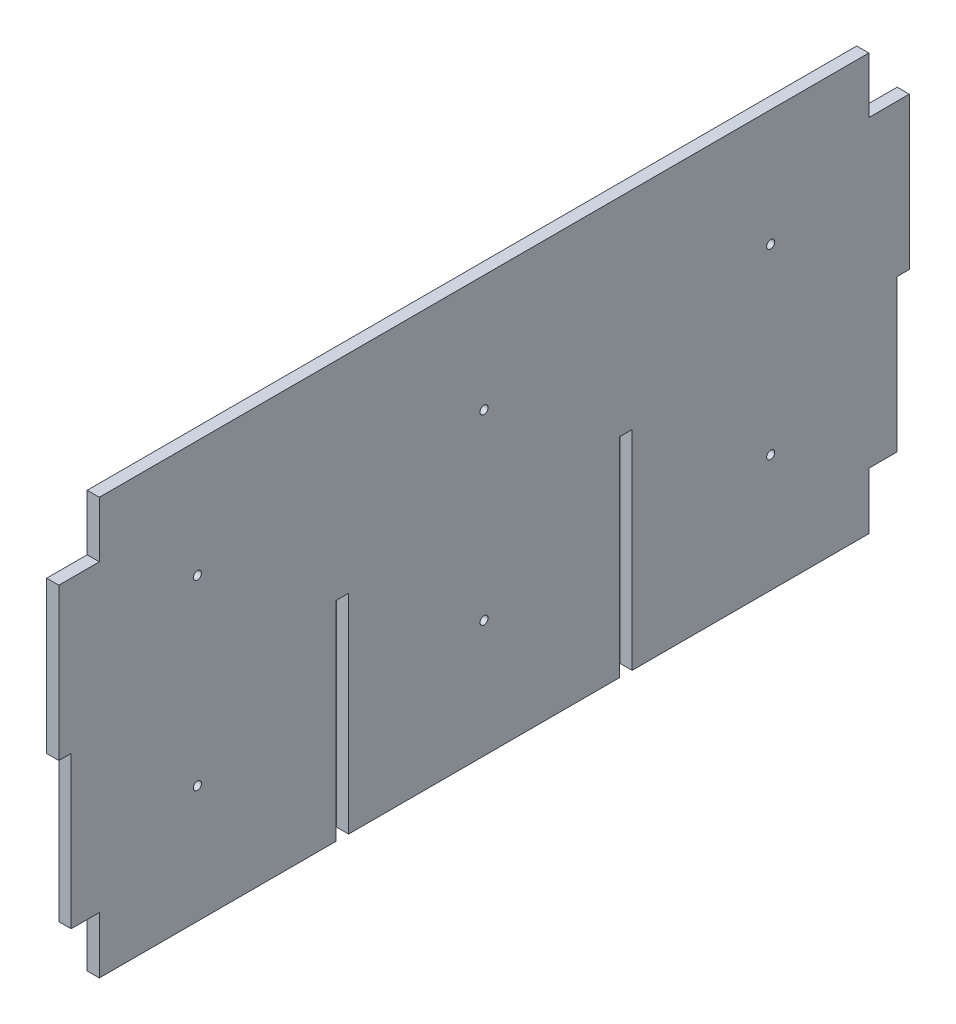
SolidWorks part; units mm, degrees
ref_plane "Front Plane" through (0, 0, 0) normal (0, 0, 1) x (1, 0, 0)
ref_plane "Top Plane" through (0, 0, 0) normal (0, 1, 0) x (1, 0, 0)
ref_plane "Right Plane" through (0, 0, 0) normal (1, 0, 0) x (0, 0, -1)
sketch "Sketch3" plane through (0, 0, 0) normal (1, 0, 0) x (0, 0, -1)
  line L1 (230.9117, 76.9159) -> (650.9117, 76.9159)
  line L2 (230.9117, 76.9159) -> (230.9117, 246.9159)
  line L3 (230.9117, 246.9159) -> (650.9117, 246.9159)
  line L4 (650.9117, 76.9159) -> (650.9117, 246.9159)
  dimension "D1" = 170
  dimension "D2" = 420
extrude "Boss-Extrude2" add sketch "Sketch3" along normal blind 6
sketch "Sketch4" plane through (6, 0, 0) normal (1, 0, 0) x (0, 0, -1)
  line L0 (230.9117, 246.9159) -> (230.9117, 76.9159) construction
  line L1 (230.9117, 161.9159) -> (237.0117, 161.9159)
  line L2 (230.9117, 161.9159) -> (230.9117, 76.9159)
  line L3 (230.9117, 76.9159) -> (237.0117, 76.9159)
  line L4 (237.0117, 161.9159) -> (237.0117, 76.9159)
  line L5 (230.9117, 76.9159) -> (650.9117, 76.9159) construction
  line L6 (650.9117, 76.9159) -> (650.9117, 246.9159) construction
  line L7 (650.9117, 161.9159) -> (644.8117, 161.9159)
  line L8 (650.9117, 161.9159) -> (650.9117, 76.9159)
  line L9 (650.9117, 76.9159) -> (644.8117, 76.9159)
  line L10 (644.8117, 161.9159) -> (644.8117, 76.9159)
  line L11 (650.9117, 246.9159) -> (230.9117, 246.9159) construction
  line L12 (367.8117, 246.9159) -> (374.0117, 246.9159)
  line L13 (367.8117, 246.9159) -> (367.8117, 161.9159)
  line L14 (367.8117, 161.9159) -> (374.0117, 161.9159)
  line L15 (374.0117, 246.9159) -> (374.0117, 161.9159)
  line L17 (514.0117, 246.9159) -> (507.8117, 246.9159)
  line L18 (514.0117, 246.9159) -> (514.0117, 161.9159)
  line L19 (514.0117, 161.9159) -> (507.8117, 161.9159)
  line L20 (507.8117, 246.9159) -> (507.8117, 161.9159)
  point P24 (370.9117, 246.9159)
  point P25 (510.9117, 246.9159)
  dimension "D1" = 6.1
  dimension "D2" = 6.1
  dimension "D3" = 140
  dimension "D4" = 140
  dimension "D5" = 6.2
  dimension "D6" = 6.2
extrude "Cut-Extrude1" cut sketch "Sketch4" against normal blind 6
sketch "Sketch5" plane through (6, 0, 0) normal (1, 0, 0) x (0, 0, -1)
  line L0 (367.8117, 246.9159) -> (230.9117, 246.9159) construction
  line L1 (237.0117, 76.9159) -> (644.8117, 76.9159) construction
  line L2 (507.8117, 246.9159) -> (374.0117, 246.9159) construction
  line L3 (650.9117, 246.9159) -> (514.0117, 246.9159) construction
  circle A0 centre (299.3617, 206.9159) radius 2
  circle A1 centre (299.3617, 116.9159) radius 2
  circle A2 centre (440.9117, 206.9159) radius 2
  circle A3 centre (582.4617, 206.9159) radius 2
  circle A4 centre (582.4617, 116.9159) radius 2
  circle A5 centre (440.9117, 116.9159) radius 2
  dimension "D7" = 4
  dimension "D8" = 4
  dimension "D9" = 4
  dimension "D10" = 4
  dimension "D11" = 4
  dimension "D12" = 4
  dimension "D1" = 40
  dimension "D2" = 40
  dimension "D3" = 40
  dimension "D4" = 40
  dimension "D5" = 40
  dimension "D6" = 40
extrude "Cut-Extrude2" cut sketch "Sketch5" against normal blind 6
sketch "Sketch6" plane through (0, 76.9159, 0) normal (0, -1, 0) x (1, 0, 0)
  line L0 (6, -237.0117) -> (6, -644.8117) construction
  line L1 (6, -250.9117) -> (0, -250.9117)
  line L2 (6, -250.9117) -> (6, -630.9117)
  line L3 (6, -630.9117) -> (0, -630.9117)
  line L4 (0, -250.9117) -> (0, -630.9117)
  line L5 (0, -237.0117) -> (0, -644.8117) construction
  dimension "D1" = 20
  dimension "D2" = 20
extrude "Boss-Extrude3" add sketch "Sketch6" along normal blind 30
sketch "Sketch7" plane through (0, 46.9159, 0) normal (0, -1, 0) x (1, 0, 0)
  line L1 (6, -250.9117) -> (0, -250.9117)
  line L2 (6, -250.9117) -> (6, -630.9117)
  line L3 (6, -630.9117) -> (0, -630.9117)
  line L4 (0, -250.9117) -> (0, -630.9117)
extrude "Cut-Extrude3" cut sketch "Sketch7" against normal blind 2
sketch "Sketch8" plane through (0, 246.9159, 0) normal (0, 1, 0) x (1, 0, 0)
  line L0 (0, 367.8117) -> (0, 230.9117) construction
  line L1 (6, 367.8117) -> (0, 367.8117)
  line L2 (6, 367.8117) -> (6, 250.9117)
  line L3 (6, 250.9117) -> (0, 250.9117)
  line L4 (0, 367.8117) -> (0, 250.9117)
  line L5 (0, 650.9117) -> (0, 514.0117) construction
  line L6 (6, 514.0117) -> (0, 514.0117)
  line L7 (6, 514.0117) -> (6, 630.9117)
  line L8 (6, 630.9117) -> (0, 630.9117)
  line L9 (0, 514.0117) -> (0, 630.9117)
  line L10 (0, 507.8117) -> (0, 374.0117) construction
  line L11 (6, 507.8117) -> (0, 507.8117)
  line L12 (6, 507.8117) -> (6, 374.0117)
  line L13 (6, 374.0117) -> (0, 374.0117)
  line L14 (0, 507.8117) -> (0, 374.0117)
  dimension "D1" = 20
  dimension "D2" = 20
extrude "Boss-Extrude4" add sketch "Sketch8" along normal blind 28
sketch "Sketch9" plane through (0, 161.9159, 0) normal (0, 1, 0) x (1, 0, 0)
  line L1 (6, 367.8117) -> (0, 367.8117)
  line L2 (6, 367.8117) -> (6, 374.0117)
  line L3 (6, 374.0117) -> (0, 374.0117)
  line L4 (0, 367.8117) -> (0, 374.0117)
extrude "Boss-Extrude5" add sketch "Sketch9" along normal blind 113
sketch "Sketch10" plane through (0, 161.9159, 0) normal (0, 1, 0) x (1, 0, 0)
  line L1 (6, 507.8117) -> (0, 507.8117)
  line L2 (6, 507.8117) -> (6, 514.0117)
  line L3 (6, 514.0117) -> (0, 514.0117)
  line L4 (0, 507.8117) -> (0, 514.0117)
extrude "Boss-Extrude6" add sketch "Sketch10" along normal blind 113
sketch "Sketch11" plane through (6, 0, 0) normal (1, 0, 0) x (0, 0, -1)
  line L0 (630.9117, 48.9159) -> (250.9117, 48.9159) construction
  line L1 (367.8117, 48.9159) -> (374.0117, 48.9159)
  line L2 (367.8117, 48.9159) -> (367.8117, 161.9159)
  line L3 (367.8117, 161.9159) -> (374.0117, 161.9159)
  line L4 (374.0117, 48.9159) -> (374.0117, 161.9159)
  line L6 (507.8117, 48.9159) -> (514.0117, 48.9159)
  line L7 (507.8117, 48.9159) -> (507.8117, 161.9159)
  line L8 (507.8117, 161.9159) -> (514.0117, 161.9159)
  line L9 (514.0117, 48.9159) -> (514.0117, 161.9159)
  dimension "D1" = 6.2
  dimension "D2" = 6.2
  dimension "D3" = 143.1
  dimension "D4" = 140
extrude "Cut-Extrude4" cut sketch "Sketch11" against normal blind 113
sketch "Sketch12" plane through (0, 0, -250.9117) normal (0, 0, 1) x (1, 0, 0)
  line L0 (6, 274.9159) -> (6, 246.9159) construction
  line L1 (0, 274.5153) -> (6, 274.5153)
  line L2 (0, 274.5153) -> (0, 264.5153)
  line L3 (0, 264.5153) -> (6, 264.5153)
  line L4 (6, 274.5153) -> (6, 264.5153)
  line L5 (0, 48.9159) -> (0, 76.9159) construction
  line L6 (6, 48.9159) -> (0, 48.9159)
  line L7 (6, 48.9159) -> (6, 58.9159)
  line L8 (6, 58.9159) -> (0, 58.9159)
  line L9 (0, 48.9159) -> (0, 58.9159)
  dimension "D1" = 10
  dimension "D2" = 10
extrude "Cut-Extrude6" cut sketch "Sketch12" against normal blind 1000
sketch "Sketch13" plane through (6, 0, 0) normal (1, 0, 0) x (0, 0, -1)
  line L0 (650.9117, 161.9159) -> (650.9117, 246.9159) construction
  line L1 (230.9117, 246.9159) -> (250.9117, 246.9159)
  line L2 (230.9117, 246.9159) -> (230.9117, 236.9159)
  line L3 (230.9117, 236.9159) -> (250.9117, 236.9159)
  line L4 (250.9117, 246.9159) -> (250.9117, 236.9159)
  line L5 (630.9117, 246.9159) -> (650.9117, 246.9159)
  line L6 (630.9117, 246.9159) -> (630.9117, 236.9159)
  line L7 (630.9117, 236.9159) -> (650.9117, 236.9159)
  line L8 (650.9117, 246.9159) -> (650.9117, 236.9159)
  line L9 (644.8117, 161.9159) -> (644.8117, 76.9159) construction
  line L10 (237.0117, 76.9159) -> (250.9117, 76.9159)
  line L11 (237.0117, 76.9159) -> (237.0117, 86.9159)
  line L12 (237.0117, 86.9159) -> (250.9117, 86.9159)
  line L13 (250.9117, 76.9159) -> (250.9117, 86.9159)
  line L14 (630.9117, 76.9159) -> (644.8117, 76.9159)
  line L15 (630.9117, 76.9159) -> (630.9117, 86.9159)
  line L16 (630.9117, 86.9159) -> (644.8117, 86.9159)
  line L17 (644.8117, 76.9159) -> (644.8117, 86.9159)
  dimension "D1" = 10
  dimension "D2" = 10
  dimension "D3" = 20
  dimension "D4" = 10
  dimension "D5" = 10
extrude "Cut-Extrude7" cut sketch "Sketch13" against normal blind 1000
